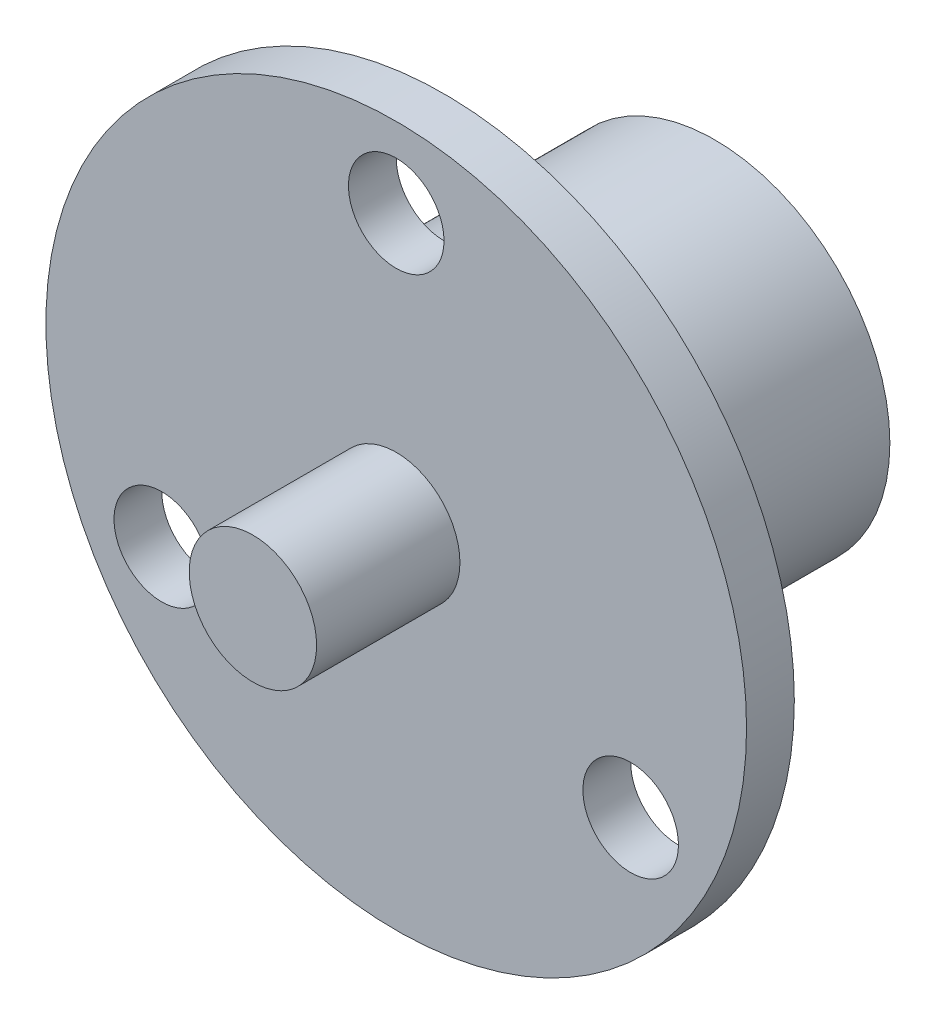
SolidWorks part; units mm, degrees
ref_plane "Plan de face" through (0, 0, 0) normal (0, 0, 1) x (1, 0, 0)
ref_plane "Plan de dessus" through (0, 0, 0) normal (0, 1, 0) x (1, 0, 0)
ref_plane "Plan de droite" through (0, 0, 0) normal (1, 0, 0) x (0, 0, -1)
sketch "Esquisse1" plane through (0, 0, 0) normal (0, 0, 1) x (1, 0, 0)
  circle A0 centre (0, 0) radius 11
  dimension "D1" = 22
extrude "Boss.-Extru.1" add sketch "Esquisse1" along normal blind 17
sketch "Esquisse2" plane through (0, 0, 17) normal (0, 0, 1) x (1, 0, 0)
  circle A0 centre (0, 0) radius 22
  dimension "D1" = 44
extrude "Boss.-Extru.2" add sketch "Esquisse2" along normal blind 3
sketch "Esquisse3" plane through (0, 0, 20) normal (0, 0, 1) x (1, 0, 0)
  circle A0 centre (0, 0) radius 4
  dimension "D1" = 8
extrude "Boss.-Extru.3" add sketch "Esquisse3" along normal blind 9
sketch "Esquisse5" plane through (0, 0, 20) normal (0, 0, 1) x (1, 0, 0)
  line L0 (0, 0) -> (0, 2.6313) construction
  line L1 (0, 0) -> (29.5537, 0) construction
  line L2 (0, 22) -> (0, 4) construction
  circle A0 centre (0, 17) radius 3
  circle A1 centre (0, 0) radius 4
  circle A2 centre (0, 0) radius 4 construction
  circle A3 centre (0, 0) radius 22
  circle A4 centre (0, 0) radius 22 construction
  circle A5 centre (14.7224, -8.5) radius 3
  circle A6 centre (-14.7224, -8.5) radius 3
  point P19 (0, 0)
  dimension "D3" = 6
  dimension "D4" = 17
  dimension "D5" = 3
  dimension "D1" = 0
  dimension "D2" = 0
extrude "Enlèv. mat.-Extru.1" cut sketch "Esquisse5" against normal up to next
